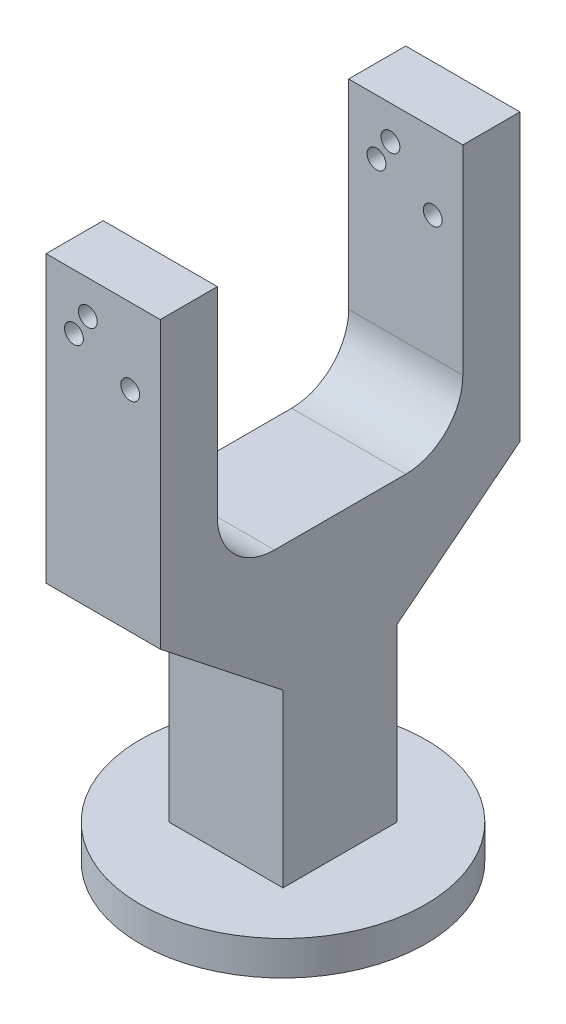
SolidWorks part; units mm, degrees
ref_plane "Front Plane" through (0, 0, 0) normal (0, 0, 1) x (1, 0, 0)
ref_plane "Top Plane" through (0, 0, 0) normal (0, 1, 0) x (1, 0, 0)
ref_plane "Right Plane" through (0, 0, 0) normal (1, 0, 0) x (0, 0, -1)
sketch "Sketch1" plane through (0, 0, 0) normal (0, 1, 0) x (1, 0, 0)
  circle A0 centre (0, 0) radius 25
  dimension "D1" = 50
extrude "Boss-Extrude1" add sketch "Sketch1" along normal blind 6
sketch "Sketch2" plane through (0, 6, 0) normal (0, 1, 0) x (1, 0, 0)
  line L1 (-10, 10) -> (10, 10)
  line L2 (-10, 10) -> (-10, -10)
  line L3 (-10, -10) -> (10, -10)
  line L4 (10, 10) -> (10, -10)
  line L5 (-10, 10) -> (10, -10) construction
  line L6 (-10, -10) -> (10, 10) construction
  point P0 (0, 0)
  dimension "D1" = 20
  dimension "D2" = 20
extrude "Boss-Extrude2" add sketch "Sketch2" along normal blind 30
ref_plane "Plane1" through (-10, 0, 0) normal (-1, 0, 0) x (0, 0, 1)
sketch "Sketch3" plane through (-10, 0, 0) normal (-1, 0, 0) x (0, 0, 1)
  line L0 (-10, 36) -> (-31.5, 52.9658)
  line L1 (-31.5, 52.9658) -> (-31.5, 102.9658)
  line L2 (-31.5, 102.9658) -> (-21.5, 102.9658)
  line L3 (-21.5, 102.9658) -> (-21.5, 58.0112)
  line L4 (-21.5, 58.0112) -> (21.5, 58.0112)
  line L5 (21.5, 102.9658) -> (21.5, 58.0112)
  line L6 (21.5, 102.9658) -> (31.5, 102.9658)
  line L7 (31.5, 102.9658) -> (31.5, 52.9658)
  line L8 (31.5, 52.9658) -> (10, 36)
  line L11 (-10, 36) -> (10, 36) construction
  line L12 (-10, 36) -> (10, 36)
  dimension "D1" = 10
  dimension "D2" = 43
  dimension "D3" = 50
  dimension "D5" = 22.0112
  dimension "D6" = 44.9545
extrude "Boss-Extrude3" add sketch "Sketch3" against normal blind 20
fillet "Fillet1" radius 10 1 edges at (0, 58.0112, -21.5)
fillet "Fillet2" radius 10 1 edges at (0, 58.0112, 21.5)
sketch "Sketch4" plane through (0, 0, 0) normal (0, -1, 0) x (1, 0, 0)
  circle A0 centre (0, 0) radius 11.1
  dimension "D1" = 22.2
extrude "Cut-Extrude1" cut sketch "Sketch4" against normal blind 2.2
sketch "Sketch5" plane through (0, 0, 31.5) normal (0, 0, 1) x (1, 0, 0)
  line L0 (-12.059, 89.6849) -> (24.0774, 89.6849) construction
  line L1 (4.7349, 89.6849) -> (-8.156, 102.5759) construction
  line L2 (4.7349, 89.6849) -> (-19.5191, 98.5126) construction
  circle A0 centre (4.7349, 89.6849) radius 1.65
  circle A1 centre (-2.6826, 97.1024) radius 1.65
  circle A2 centre (-5.1224, 93.2727) radius 1.65
  point P10 (4.7933, 90.542)
  point P11 (4.7349, 89.6849)
  dimension "D1" = 3.3
  dimension "D3" = 3.3
  dimension "D6" = 3.3
  dimension "D2" = 45
  dimension "D4" = 10.49
  dimension "D5" = 20
  dimension "D7" = 10.49
extrude "Cut-Extrude2" cut sketch "Sketch5" against normal blind 80
equation "\"1i\"=2"
